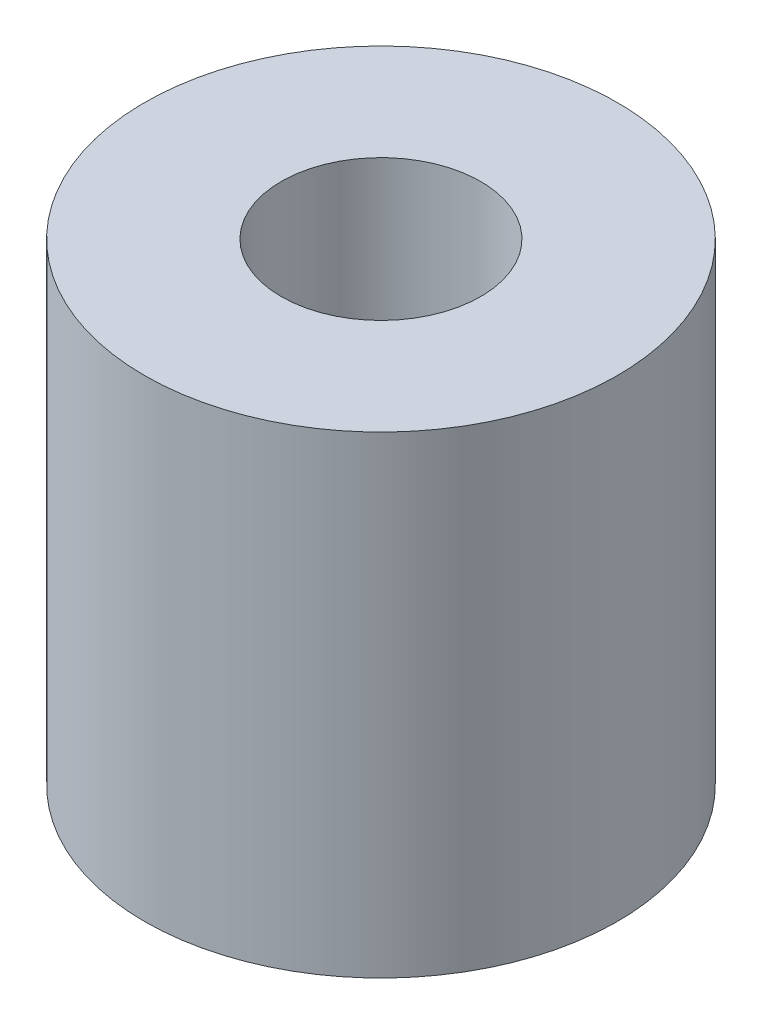
SolidWorks part; units mm, degrees
material "6061-T6 (SS)"
ref_plane "Front" through (0, 0, 0) normal (0, 0, 1) x (1, 0, 0)
ref_plane "Top" through (0, 0, 0) normal (0, 1, 0) x (1, 0, 0)
ref_plane "Right" through (0, 0, 0) normal (1, 0, 0) x (0, 0, -1)
sketch "Sketch1" plane through (0, 0, 0) normal (0, 1, 0) x (1, 0, 0)
  circle A0 centre (0, 0) radius 12.7
  dimension "D1" = 25.4
extrude "Boss-Extrude1" add sketch "Sketch1" along normal blind 25.4
hole_wizard "1/2-13 Tapped Hole1" positions "Sketch2" profile "Sketch3" tap size "1/2-13" standard "ANSI Inch" end condition through all
sketch "Sketch2" plane through (0, 25.4, 0) normal (0, 1, 0) x (1, 0, 0)
  point P0 (0, 0)
sketch "Sketch3" plane through (0, 25.4, 0) normal (1, 0, 0) x (0, 0, 1)
  line L0 (0, 0) -> (0, 25.4)
  line L1 (0, 25.4) -> (5.3581, 25.4)
  line L2 (5.3581, 25.4) -> (5.3581, 0)
  line L5 (5.3581, 0) -> (0, 0)
  line L11 (0, -6.35) -> (0, 107.95) construction
  dimension "Thru Tap Drill Dia." = 10.7163
  dimension "Thru Tap Drill Depth" = 25.4
cosmetic thread "Hole Thread1"
